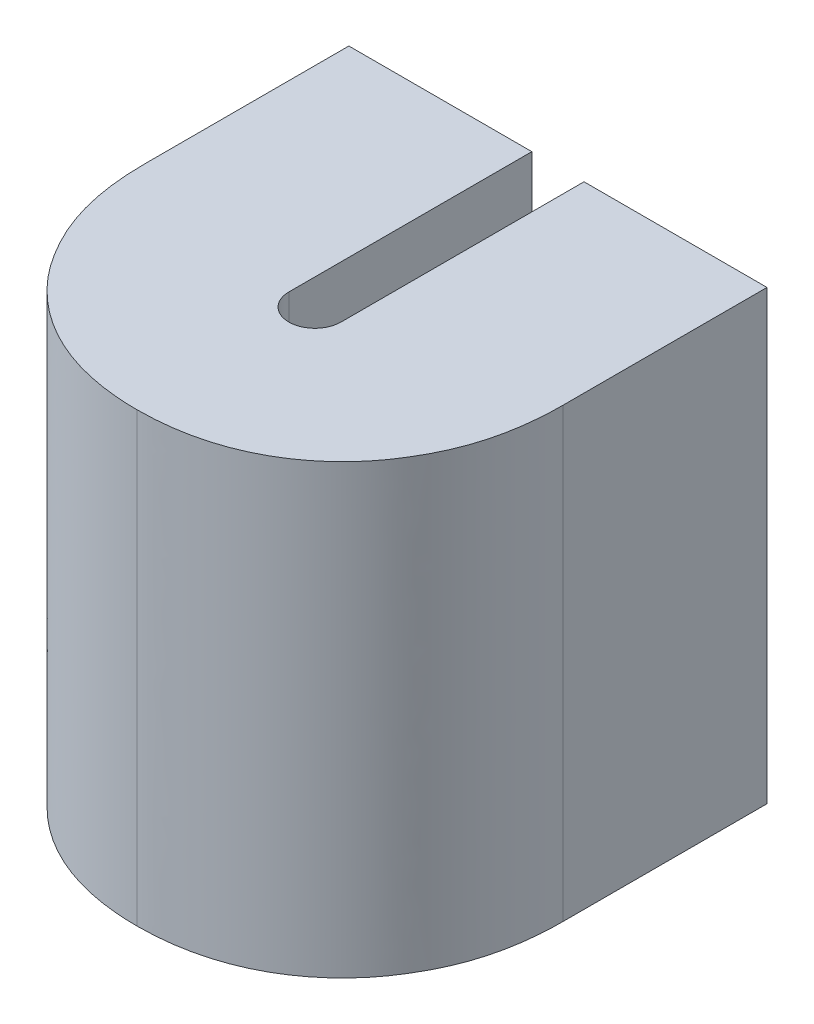
SolidWorks part; units mm, degrees
ref_plane "Front" through (0, 0, 0) normal (0, 0, 1) x (1, 0, 0)
ref_plane "Top" through (0, 0, 0) normal (0, 1, 0) x (1, 0, 0)
ref_plane "Right" through (0, 0, 0) normal (1, 0, 0) x (0, 0, -1)
sketch "Sketch1" plane through (0, 0, 0) normal (0, 1, 0) x (1, 0, 0)
  line L0 (701.3369, 727.7334) -> (701.3369, 1412)
  line L1 (701.3369, 1412) -> (87.5, 1412)
  line L2 (87.5, 1412) -> (87.5, 596.8398)
  line L3 (0, 939.642) -> (0, -1120.5477) construction
  line L4 (-233.8778, 0) -> (286.2747, 0) construction
  line L5 (701.3369, -112.4389) -> (701.3369, 193.3205) construction
  line L6 (-701.3369, 727.7334) -> (-701.3369, 1412)
  line L7 (-87.5, 1412) -> (-87.5, 596.8398)
  line L8 (-701.3369, 1412) -> (-87.5, 1412)
  arc A0 (87.5, 596.8398) -> (-87.5, 596.8398) centre (0, 596.8398) cw
  spline S0 degree 3 poles (701.3369, 727.7334) (701.3369, 516.522) (626.8023, 362.4883) (504.7353, 189.7298) (300.8281, 0) (0, 0) knots 0 0 0 0 0.501135 0.601135 1 1 1 1
  spline S1 degree 3 poles (-701.3369, 727.7334) (-701.3369, 516.522) (-626.8023, 362.4883) (-504.7353, 189.7298) (-300.8281, 0) (0, 0) knots 0 0 0 0 0.501135 0.601135 1 1 1 1
  point P10 (0, 596.8398)
  dimension "D5" = 704.0381
  dimension "D6" = 704.0381
  dimension "D7" = 1002.7602
  dimension "D10" = 87.5
  dimension "D1" = 87.5
  dimension "D2" = 596.8398
  dimension "D3" = 130.8936
  dimension "D4" = 701.3369
  dimension "D8" = 556.4571
  dimension "D9" = 333.1067
  dimension "D11" = 1412
extrude "Boss-Extrude1" add sketch "Sketch1" along normal blind 1500
equation "\"Height\"= 1500"
equation "\"D1@Boss-Extrude1\"=\"Height\""
